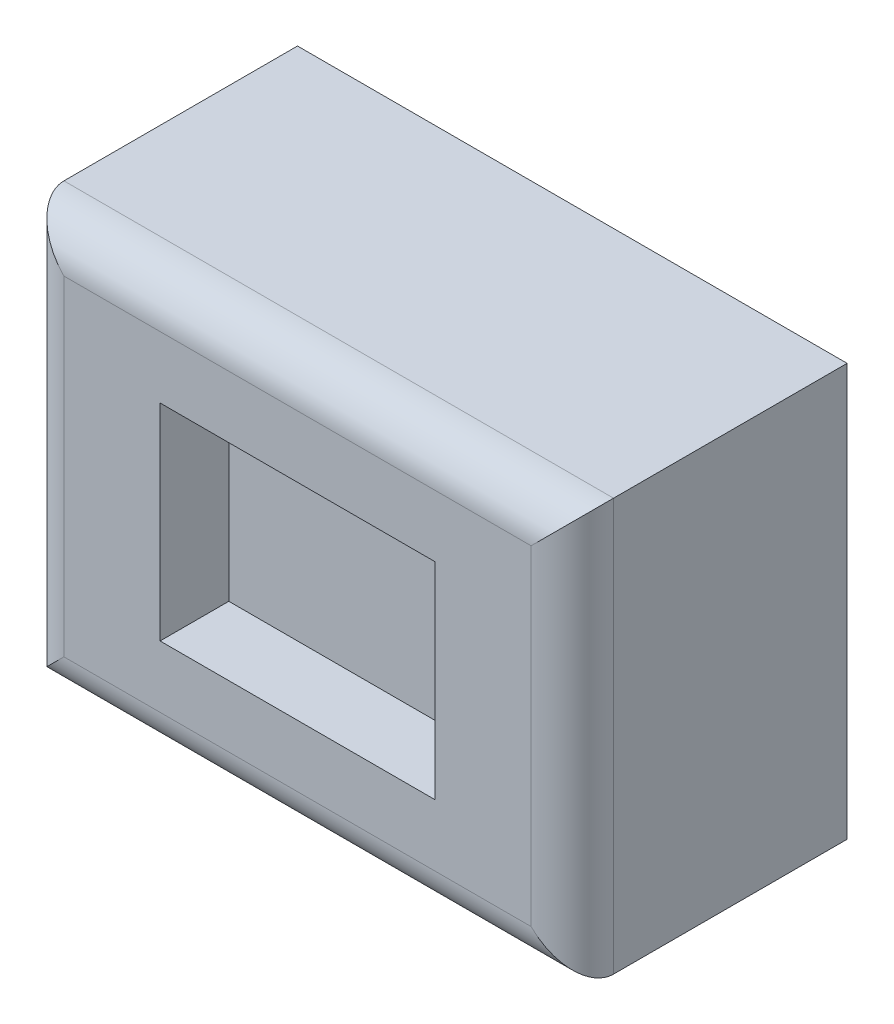
SolidWorks part; units mm, degrees
ref_plane "正面" through (0, 0, 0) normal (0, 0, 1) x (1, 0, 0)
ref_plane "平面" through (0, 0, 0) normal (0, 1, 0) x (1, 0, 0)
ref_plane "右側面" through (0, 0, 0) normal (1, 0, 0) x (0, 0, -1)
sketch "ｽｹｯﾁ1" plane through (0, 0, 0) normal (0, 0, 1) x (1, 0, 0)
  line L1 (-20, -15) -> (20, -15)
  line L2 (-20, -15) -> (-20, 15)
  line L3 (-20, 15) -> (20, 15)
  line L4 (20, -15) -> (20, 15)
extrude "M0_Boss" add sketch "ｽｹｯﾁ1" along normal blind 20
sketch "ｽｹｯﾁ2" plane through (0, 0, 20) normal (0, 0, 1) x (1, 0, 0)
  line L1 (-10, -7.5) -> (10, -7.5)
  line L2 (-10, -7.5) -> (-10, 7.5)
  line L3 (-10, 7.5) -> (10, 7.5)
  line L4 (10, -7.5) -> (10, 7.5)
extrude "M0_Pocket" cut sketch "ｽｹｯﾁ2" against normal blind 5
fillet "M0_TopR3" radius 3 4 edges at (-20, 0, 20) (0, -15, 20) (20, 0, 20) (0, 15, 20)
